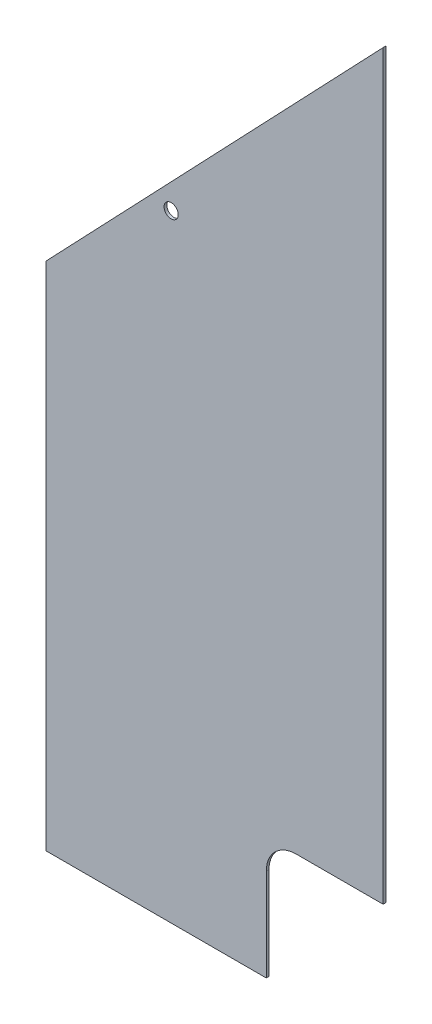
SolidWorks part; units mm, degrees
material "PC High Viscosity"
ref_plane "Front Plane" through (0, 0, 0) normal (0, 0, 1) x (1, 0, 0)
ref_plane "Top Plane" through (0, 0, 0) normal (0, 1, 0) x (1, 0, 0)
ref_plane "Right Plane" through (0, 0, 0) normal (1, 0, 0) x (0, 0, -1)
sketch "Sketch1" plane through (0, 0, 0) normal (0, 0, 1) x (1, 0, 0)
  line L0 (0, 0) -> (-393.7, 0)
  line L1 (-393.7, 0) -> (-393.7, 596.9)
  line L2 (-393.7, 596.9) -> (0, 1009.65)
  line L4 (0, 1009.65) -> (0, 0)
  dimension "D1" = 596.9
  dimension "D2" = 393.7
  dimension "D3" = 1009.65
extrude "Boss-Extrude1" add sketch "Sketch1" along normal blind 3.175
sketch "Sketch2" plane through (0, 0, 3.175) normal (0, 0, 1) x (1, 0, 0)
  line L0 (-393.7, 0) -> (0, 0) construction
  line L1 (-114.3, 101.6) -> (-88.9, 101.6)
  line L2 (-114.3, 101.6) -> (-114.3, 0)
  line L3 (-114.3, 0) -> (-88.9, 0)
  line L4 (-88.9, 101.6) -> (-88.9, 0)
  line L5 (-114.3, 101.6) -> (-88.9, 0) construction
  line L6 (-114.3, 0) -> (-88.9, 101.6) construction
  line L8 (-101.6, 101.6) -> (-101.6, 0) construction
  line L9 (-393.7, 596.9) -> (-393.7, 0) construction
  point P0 (-101.6, 50.8)
  dimension "D1" = 25.4
  dimension "D2" = 292.1
  dimension "D3" = 101.6
extrude "Cut-Extrude1" [suppressed] cut sketch "Sketch2" against normal through all
fillet "Fillet1" [suppressed] radius 12.7
sketch "Sketch4" plane through (0, 0, 3.175) normal (0, 0, 1) x (1, 0, 0)
  line L2 (-371.475, 579.7602) -> (-371.475, 620.2004)
  line L3 (-393.7, 66.675) -> (-381, 66.675)
  line L4 (-374.65, 73.025) -> (-374.65, 79.375)
  line L5 (-381, 85.725) -> (-393.7, 85.725)
  line L6 (-393.7, 85.725) -> (-393.7, 66.675)
  line L7 (-393.7, 0) -> (0, 0) construction
  line L8 (-393.7, 596.9) -> (-393.7, 0) construction
  line L9 (-393.7, 567.0602) -> (-384.175, 567.0602)
  line L10 (-371.475, 620.2004) -> (-393.7, 596.9)
  line L12 (-393.7, 596.9) -> (-393.7, 567.0602)
  line L13 (0, 1009.65) -> (-393.7, 596.9) construction
  arc A1 (-384.175, 567.0602) -> (-371.475, 579.7602) centre (-384.175, 579.7602) ccw
  arc A2 (-381, 66.675) -> (-374.65, 73.025) centre (-381, 73.025) ccw
  arc A3 (-374.65, 79.375) -> (-381, 85.725) centre (-381, 79.375) ccw
  point P20 (-393.7, 581.9801)
  dimension "D4" = 6.35
  dimension "D8" = 12.7
  dimension "D1" = 19.05
  dimension "D2" = 12.7
  dimension "D3" = 66.675
  dimension "D9" = 22.225
  dimension "D10" = 29.8398
sketch "Sketch3" [suppressed] plane through (0, 0, 0) normal (0, 0, 1) x (1, 0, 0)
  line L0 (0, 1009.65) -> (-395.2875, 622.3)
  line L1 (0, 0) -> (-1219.2, 0)
  line L2 (0, 0) -> (0, 2438.4)
  line L3 (0, 2438.4) -> (-1219.2, 2438.4)
  line L4 (-1219.2, 0) -> (-1219.2, 2438.4)
  line L5 (0, 1009.65) -> (-395.2875, 622.3) construction
  line L6 (-395.2875, 622.3) -> (-395.2875, 1612.9)
  line L7 (-395.2875, 1612.9) -> (0, 1612.9)
  line L8 (0, 1612.9) -> (0, 1009.65)
  line L9 (-395.2875, 622.3) -> (-395.2875, 0) construction
  line L11 (-401.6375, 1612.9) -> (-796.925, 1612.9)
  line L12 (-401.6375, 1612.9) -> (-401.6375, 0)
  line L13 (-401.6375, 0) -> (-796.925, 0)
  line L14 (-796.925, 1612.9) -> (-796.925, 0)
  line L15 (-823.9125, 1612.9) -> (-1219.2, 1612.9)
  line L16 (-823.9125, 1612.9) -> (-823.9125, 0)
  line L17 (-823.9125, 0) -> (-1219.2, 0)
  line L18 (-1219.2, 1612.9) -> (-1219.2, 0)
  line L19 (0, 1641.0222) -> (-990.6, 1641.0222)
  line L20 (0, 1641.0222) -> (0, 2031.6742)
  line L21 (0, 2031.6742) -> (-990.6, 2031.6742)
  line L22 (-990.6, 1641.0222) -> (-990.6, 2031.6742)
  line L23 (0, 2047.748) -> (-991.848, 2047.748)
  line L24 (0, 2047.748) -> (0, 2438.4)
  line L25 (0, 2438.4) -> (-991.848, 2438.4)
  line L26 (-991.848, 2047.748) -> (-991.848, 2438.4)
  dimension "D1" = 1219.2
  dimension "D2" = 2438.4
  dimension "D3" = 990.6
  dimension "D4" = 6.35
  dimension "D5" = 990.6
  dimension "D6" = 390.652
extrude "Cut-Extrude2" [suppressed] cut sketch "Sketch4" against normal through all
sketch "Sketch5" plane through (0, 0, 3.175) normal (0, 0, 1) x (1, 0, 0)
  circle A1 centre (-247.65, 720.725) radius 8.255
  circle A2 centre (-247.65, 720.725) radius 3.2639 construction
  dimension "D1" = 16.51
extrude "Cut-Extrude3" cut sketch "Sketch5" against normal through all
sketch "Sketch6" plane through (0, 0, 3.175) normal (0, 0, 1) x (1, 0, 0)
  line L6 (0, 0) -> (0, 1009.65) construction
  line L9 (0, 142.875) -> (-101.6, 142.875)
  line L10 (-136.525, 107.95) -> (-136.525, 0)
  line L11 (-393.7, 0) -> (0, 0) construction
  line L12 (0, 142.875) -> (0, 0)
  line L13 (0, 0) -> (-136.525, 0)
  arc A0 (-101.6, 142.875) -> (-136.525, 107.95) centre (-101.6, 107.95) ccw
  dimension "D1" = 34.925
  dimension "D2" = 136.525
  dimension "D3" = 142.875
extrude "Cut-Extrude4" cut sketch "Sketch6" against normal through all
